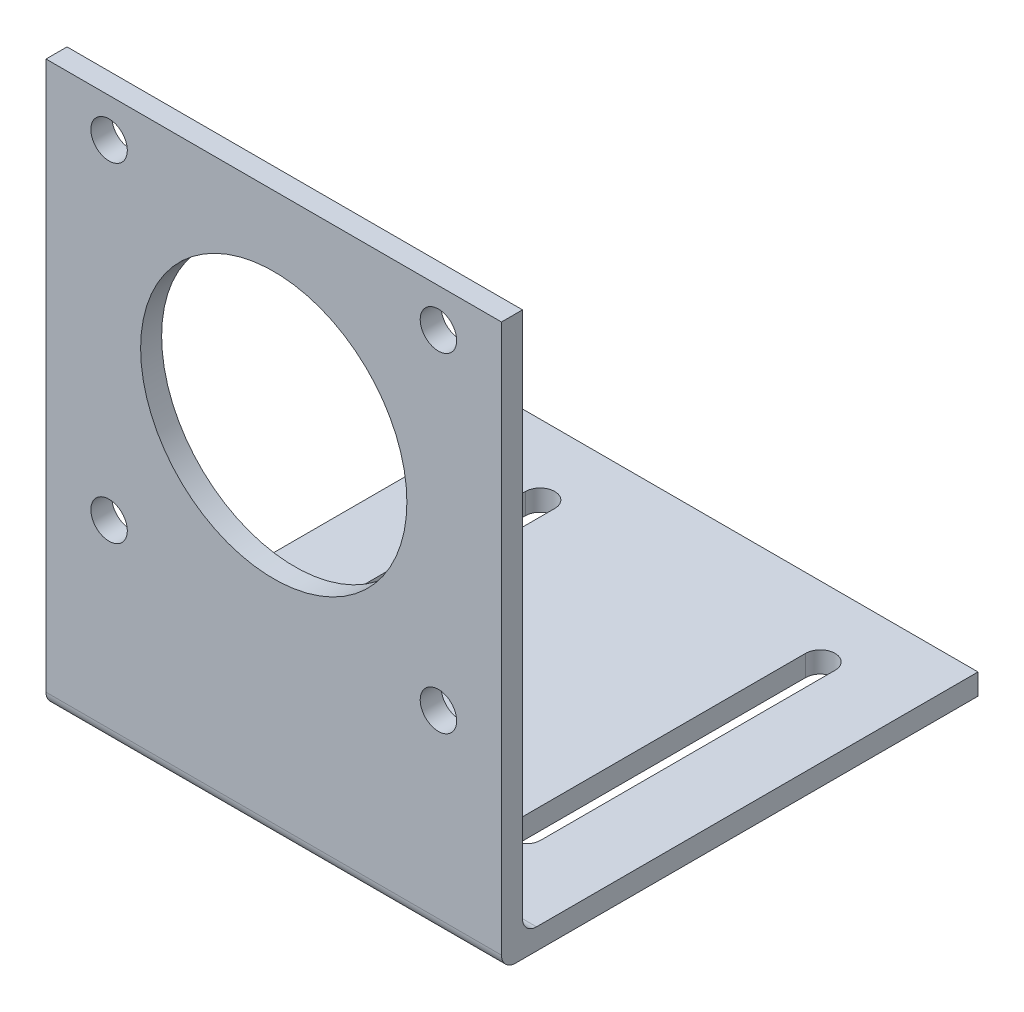
SolidWorks part; units mm, degrees
ref_plane "Front Plane" through (0, 0, 0) normal (0, 0, 1) x (1, 0, 0)
ref_plane "Top Plane" through (0, 0, 0) normal (0, 1, 0) x (1, 0, 0)
ref_plane "Right Plane" through (0, 0, 0) normal (1, 0, 0) x (0, 0, -1)
sketch "Sketch1" plane through (0, 0, 0) normal (1, 0, 0) x (0, 0, -1)
  line L0 (0, 0) -> (-66, 0)
  line L1 (-68, 2) -> (-68, 80.25)
  line L2 (0, 0) -> (0, 3)
  line L3 (-68, 80.25) -> (-65, 80.25)
  line L4 (-65, 80.25) -> (-65, 5)
  line L5 (-63, 3) -> (0, 3)
  arc A0 (-66, 0) -> (-68, 2) centre (-66, 2) cw
  arc A1 (-63, 3) -> (-65, 5) centre (-63, 5) cw
  point P9 (-68, 0)
  dimension "D5" = 2
  dimension "D1" = 68
  dimension "D2" = 80.25
  dimension "D3" = 3
  dimension "D4" = 3
extrude "Body" add sketch "Sketch1" along normal blind 65
sketch "Sketch4" plane through (0, 3, 0) normal (0, 1, 0) x (1, 0, 0)
  line L2 (50.4, -52) -> (50.4, -10)
  line L3 (54.6, -52) -> (54.6, -10)
  line L4 (10.4, -52) -> (10.4, -10)
  line L6 (14.6, -52) -> (14.6, -10)
  arc A0 (10.4, -10) -> (14.6, -10) centre (12.5, -10) cw
  arc A1 (10.4, -52) -> (14.6, -52) centre (12.5, -52) ccw
  arc A2 (54.6, -52) -> (50.4, -52) centre (52.5, -52) cw
  arc A3 (54.6, -10) -> (50.4, -10) centre (52.5, -10) ccw
  dimension "D1" = 42
  dimension "D2" = 4.2
extrude "Cut-Extrude1" cut sketch "Sketch4" against normal blind 3
sketch "Sketch5" plane through (0, 0, 65) normal (0, 0, -1) x (-1, 0, 0)
  line L0 (-65, 80.25) -> (0, 80.25) construction
  line L1 (0, 5) -> (0, 80.25) construction
  circle A0 centre (-32.5, 51.25) radius 19
  circle A1 centre (-9, 74.75) radius 2.6
  circle A2 centre (-56, 74.75) radius 2.6
  circle A3 centre (-56, 27.75) radius 2.6
  circle A4 centre (-9, 27.75) radius 2.6
  point P2 (0, 0)
  point P7 (0, 0)
  point P16 (0, 0)
  point P17 (0, 0)
  point P18 (0, 0)
  point P19 (0, 0)
  point P20 (0, 0)
  point P21 (-32.5, 39)
  point P22 (0, 0)
  point P23 (0, 0)
  dimension "D1" = 38
  dimension "D5" = 5.2
  dimension "D6" = 9
  dimension "D8" = 32.5
  dimension "D2" = 29
  dimension "D3" = 47
  dimension "D4" = 47
  dimension "D7" = 5.5
extrude "Cut-Extrude2" cut sketch "Sketch5" against normal blind 3
